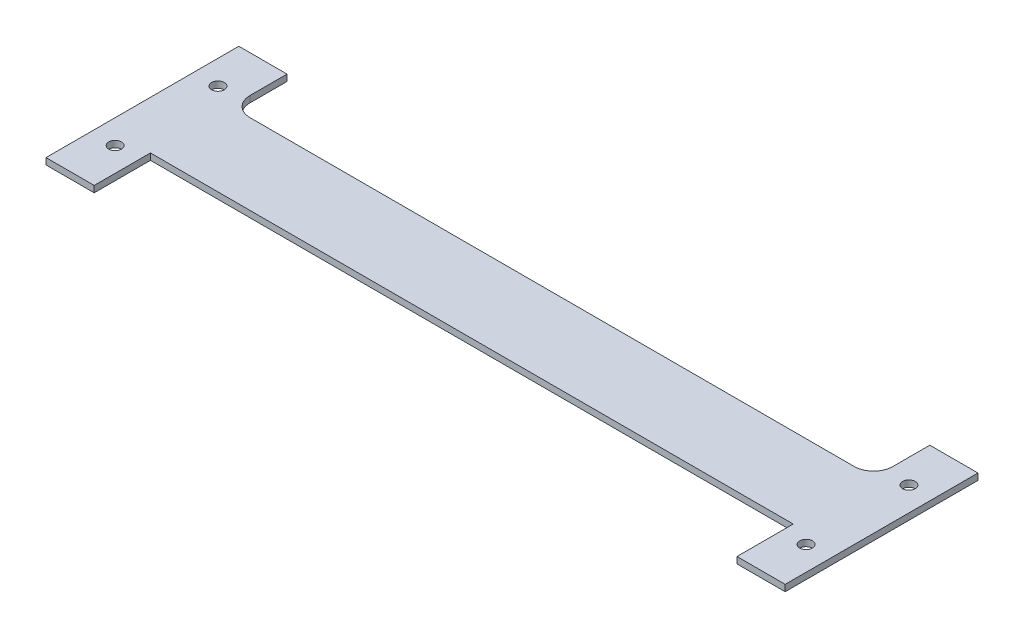
SolidWorks part; units mm, degrees
ref_plane "Front Plane" through (0, 0, 0) normal (0, 0, 1) x (1, 0, 0)
ref_plane "Top Plane" through (0, 0, 0) normal (0, 1, 0) x (1, 0, 0)
ref_plane "Right Plane" through (0, 0, 0) normal (1, 0, 0) x (0, 0, -1)
sketch "Sketch1" plane through (0, 0, 0) normal (0, 1, 0) x (1, 0, 0)
  line L0 (-127, 38.1) -> (-127, 23.495)
  line L1 (-127, -15.875) -> (127, -15.875)
  line L3 (-119.38, 15.875) -> (119.38, 15.875)
  line L5 (-127, -15.875) -> (127, 15.875) construction
  line L6 (-127, 15.875) -> (127, -15.875) construction
  line L7 (-127, 38.1) -> (-146.05, 38.1)
  line L8 (-127, -38.1) -> (-146.05, -38.1)
  line L9 (-146.05, 38.1) -> (-146.05, -38.1)
  line L10 (127, 38.1) -> (127, 23.495)
  line L11 (127, 38.1) -> (146.05, 38.1)
  line L12 (127, -38.1) -> (146.05, -38.1)
  line L13 (146.05, 38.1) -> (146.05, -38.1)
  line L14 (0, 15.875) -> (0, -15.875) construction
  line L16 (-127, -15.875) -> (-127, -38.1)
  line L17 (127, -15.875) -> (127, -38.1)
  circle A0 centre (136.525, 20.32) radius 2.5
  circle A1 centre (136.525, -20.32) radius 2.5
  circle A2 centre (-136.525, 20.32) radius 2.5
  circle A3 centre (-136.525, -20.32) radius 2.5
  arc A4 (119.38, 15.875) -> (127, 23.495) centre (119.38, 23.495) ccw
  arc A5 (-127, 23.495) -> (-119.38, 15.875) centre (-119.38, 23.495) ccw
  point P0 (0, 0)
  dimension "D10" = 5
  dimension "D11" = 5
  dimension "D8" = 7.62
  dimension "D1" = 254
  dimension "D2" = 31.75
  dimension "D3" = 19.05
  dimension "D4" = 19.05
  dimension "D5" = 40.64
  dimension "D6" = 76.2
  dimension "D7" = 9.525
  dimension "D9" = 38.1
  dimension "D12" = 9.525
  dimension "D13" = 20.32
  dimension "D14" = 38.1
extrude "Boss-Extrude1" add sketch "Sketch1" along normal blind 2.54
